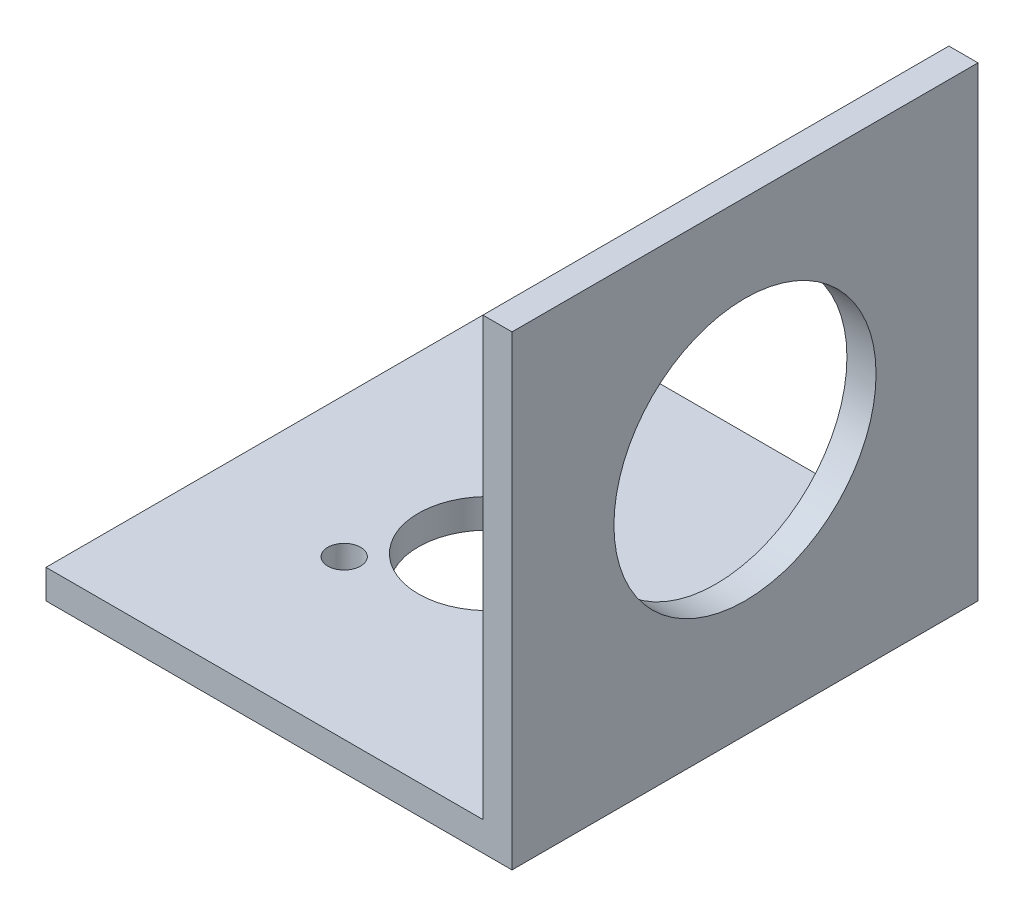
SolidWorks part; units mm, degrees
ref_plane "Front Plane" through (0, 0, 0) normal (0, 0, 1) x (1, 0, 0)
ref_plane "Top Plane" through (0, 0, 0) normal (0, 1, 0) x (1, 0, 0)
ref_plane "Right Plane" through (0, 0, 0) normal (1, 0, 0) x (0, 0, -1)
sketch "Sketch1" plane through (0, 0, 0) normal (0, 0, 1) x (1, 0, 0)
  line L1 (0, 0) -> (50.8, 0)
  line L2 (0, 0) -> (0, 3.175)
  line L3 (0, 3.175) -> (47.625, 3.175)
  line L4 (50.8, 0) -> (50.8, 3.175)
  line L5 (50.8, 0) -> (47.625, 0)
  line L6 (50.8, 0) -> (50.8, 50.8)
  line L7 (50.8, 50.8) -> (47.625, 50.8)
  line L8 (47.625, 3.175) -> (47.625, 50.8)
  dimension "D1" = 50.8
  dimension "D2" = 3.175
  dimension "D3" = 3.175
  dimension "D4" = 50.8
extrude "Boss-Extrude1" add sketch "Sketch1" along normal blind 50.8 contours L8 L3 L2 L1 L4 L6 L7
sketch "Sketch2" plane through (47.625, 0, 0) normal (-1, 0, 0) x (0, 0, 1)
  circle A0 centre (25.4, 26.9875) radius 14.2875
  dimension "D1" = 28.575
extrude "Cut-Extrude1" cut sketch "Sketch2" against normal blind 50.8
sketch "Sketch3" plane through (0, 3.175, 0) normal (0, 1, 0) x (1, 0, 0)
  line L0 (0, -50.8) -> (0, 0) construction
  circle A0 centre (22.8092, -25.4) radius 7.62
  dimension "D1" = 15.24
  dimension "D2" = 22.8092
extrude "Cut-Extrude2" cut sketch "Sketch3" against normal blind 50.8
sketch "Sketch4" plane through (0, 0, 0) normal (0, -1, 0) x (1, 0, 0)
  circle A0 centre (15.2504, 33.5457) radius 1.7859
  circle A1 centre (19.5342, 14.781) radius 1.7859
  circle A2 centre (33.643, 27.8733) radius 1.7859
extrude "Cut-Extrude3" cut sketch "Sketch4" against normal blind 12.7
